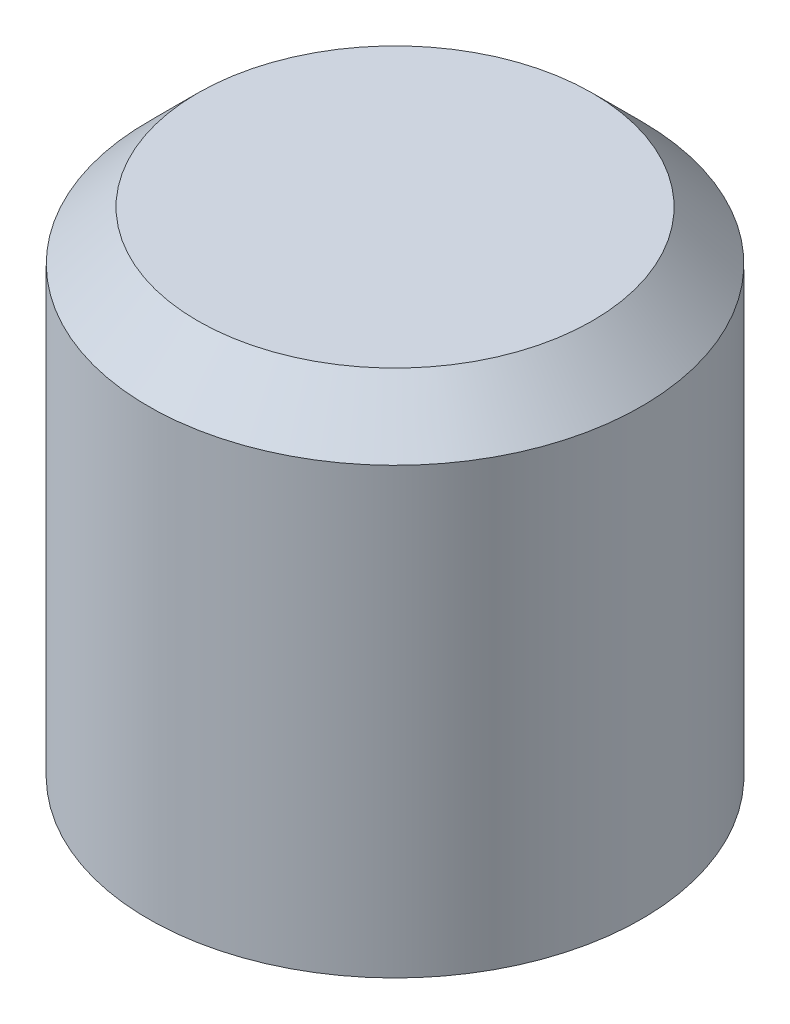
SolidWorks part; units mm, degrees
ref_plane "Front Plane" through (0, 0, 0) normal (0, 0, 1) x (1, 0, 0)
ref_plane "Top Plane" through (0, 0, 0) normal (0, 1, 0) x (1, 0, 0)
ref_plane "Right Plane" through (0, 0, 0) normal (1, 0, 0) x (0, 0, -1)
ref_plane "plane:xy" through (0, 0, 0) normal (0, 0, 1) x (1, 0, 0)
sketch "sketch:profile" plane through (0, 0, 0) normal (0, 0, 1) x (1, 0, 0)
  line L0 (0, 0) -> (10, 0)
  line L1 (10, 0) -> (10, 18)
  line L2 (10, 18) -> (8, 20)
  line L3 (8, 20) -> (0, 20)
  line L4 (0, 20) -> (0, 0)
  line L5 (0, -10) -> (0, 30) construction
revolve "feature:turned" add sketch "sketch:profile" angle 360 about L5
fillet "feature:round" [suppressed] radius 1
sketch "sketch:helper-0" plane through (0, 0, 0) normal (0, 0, 1) x (1, 0, 0)
  line L0 (30, 0) -> (40, 0)
sketch "sketch:helper-1" plane through (0, 0, 0) normal (0, 0, 1) x (1, 0, 0)
  line L0 (30, 5) -> (40, 5)
